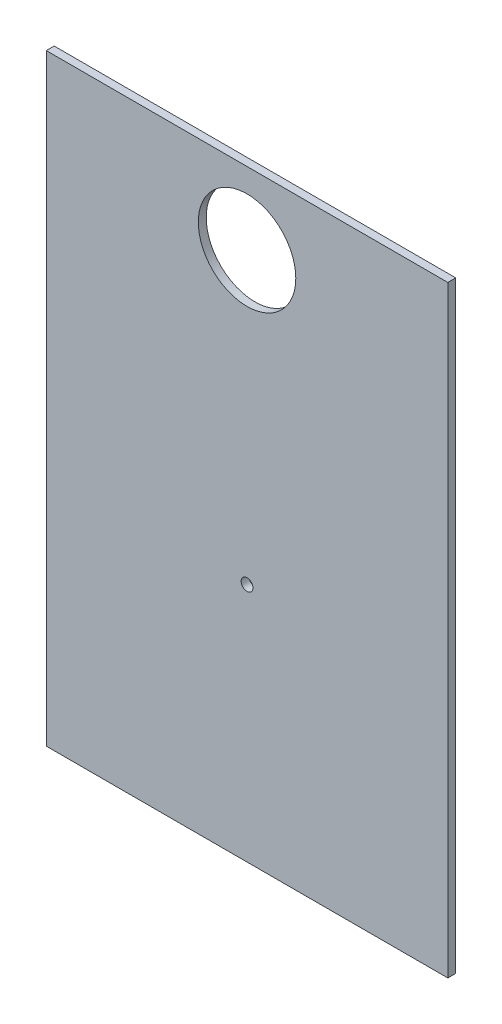
SolidWorks part; units mm, degrees
material "Acrylic (Medium-high impact)"
ref_plane "Front Plane" through (0, 0, 0) normal (0, 0, 1) x (1, 0, 0)
ref_plane "Top Plane" through (0, 0, 0) normal (0, 1, 0) x (1, 0, 0)
ref_plane "Right Plane" through (0, 0, 0) normal (1, 0, 0) x (0, 0, -1)
sketch "Sketch1" plane through (0, 0, 0) normal (0, 0, 1) x (1, 0, 0)
  line L1 (152.4, -228.6) -> (-152.4, -228.6)
  line L2 (152.4, -228.6) -> (152.4, 228.6)
  line L3 (152.4, 228.6) -> (-152.4, 228.6)
  line L4 (-152.4, -228.6) -> (-152.4, 228.6)
  line L5 (152.4, -228.6) -> (-152.4, 228.6) construction
  line L6 (152.4, 228.6) -> (-152.4, -228.6) construction
  point P0 (0, 0)
  dimension "D1" = 457.2
  dimension "D2" = 304.8
extrude "Boss-Extrude1" add sketch "Sketch1" along normal blind 6
sketch "Sketch2" plane through (0, 0, 6) normal (0, 0, 1) x (1, 0, 0)
  line L0 (-152.4, 173.6) -> (152.4, 173.6) construction
  line L1 (-152.4, 228.6) -> (-152.4, -228.6) construction
  line L2 (152.4, -228.6) -> (152.4, 228.6) construction
  line L3 (152.4, 228.6) -> (-152.4, 228.6) construction
  circle A0 centre (0, 173.6) radius 37
  dimension "D2" = 74
  dimension "D1" = 55
extrude "Cut-Extrude1" cut sketch "Sketch2" against normal through all
sketch "Sketch3" plane through (0, 0, 6) normal (0, 0, 1) x (1, 0, 0)
  line L0 (-152.4, -76.2) -> (152.4, -76.2) construction
  line L1 (-152.4, 228.6) -> (-152.4, -228.6) construction
  line L2 (152.4, -228.6) -> (152.4, 228.6) construction
  line L3 (-152.4, -228.6) -> (152.4, -228.6) construction
  circle A0 centre (0, -46.2) radius 4.5
  point P10 (0, -76.2)
  dimension "D3" = 9
  dimension "D1" = 152.4
  dimension "D2" = 30
extrude "Cut-Extrude2" cut sketch "Sketch3" against normal through all
